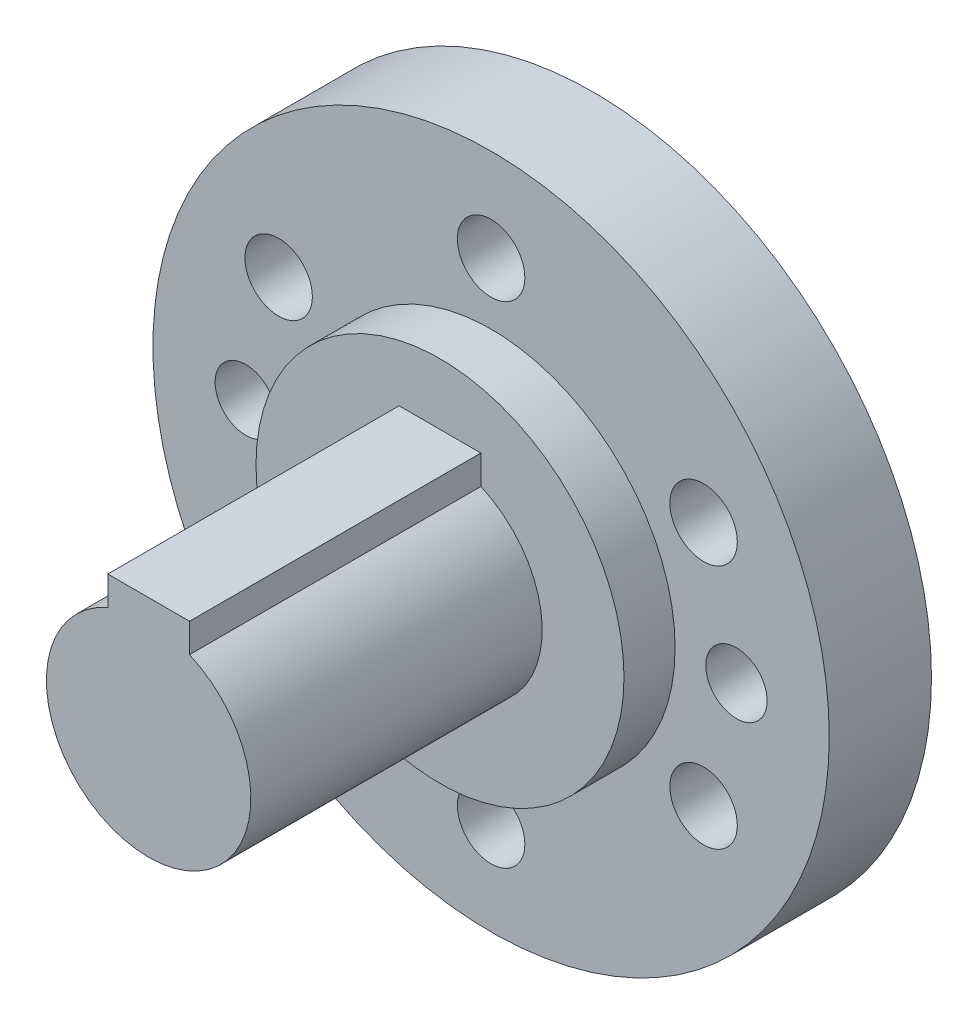
SolidWorks part; units mm, degrees
ref_plane "Front Plane" through (0, 0, 0) normal (0, 0, 1) x (1, 0, 0)
ref_plane "Top Plane" through (0, 0, 0) normal (0, 1, 0) x (1, 0, 0)
ref_plane "Right Plane" through (0, 0, 0) normal (1, 0, 0) x (0, 0, -1)
sketch "Sketch1" plane through (0, 0, 0) normal (0, 0, 1) x (1, 0, 0)
  arc A0 (9, 0) -> (-9, 0) centre (0, 0) ccw
  arc A1 (-9, 0) -> (9, 0) centre (0, 0) ccw
  arc A2 (1.65, 12) -> (-1.65, 12) centre (0, 12) ccw
  arc A3 (-1.65, 12) -> (1.65, 12) centre (0, 12) ccw
  arc A4 (11.2173, 4.5711) -> (9.5673, 7.4289) centre (10.3923, 6) ccw
  arc A5 (9.5673, 7.4289) -> (11.2173, 4.5711) centre (10.3923, 6) ccw
  arc A6 (9.5673, -7.4289) -> (11.2173, -4.5711) centre (10.3923, -6) ccw
  arc A7 (11.2173, -4.5711) -> (9.5673, -7.4289) centre (10.3923, -6) ccw
  arc A8 (-1.65, -12) -> (1.65, -12) centre (0, -12) ccw
  arc A9 (1.65, -12) -> (-1.65, -12) centre (0, -12) ccw
  arc A10 (-11.2173, -4.5711) -> (-9.5673, -7.4289) centre (-10.3923, -6) ccw
  arc A11 (-9.5673, -7.4289) -> (-11.2173, -4.5711) centre (-10.3923, -6) ccw
  arc A12 (-9.5673, 7.4289) -> (-11.2173, 4.5711) centre (-10.3923, 6) ccw
  arc A13 (-11.2173, 4.5711) -> (-9.5673, 7.4289) centre (-10.3923, 6) ccw
  arc A14 (13.5, 0) -> (10.5, 0) centre (12, 0) ccw
  arc A15 (10.5, 0) -> (13.5, 0) centre (12, 0) ccw
  arc A16 (-10.5, 0) -> (-13.5, 0) centre (-12, 0) ccw
  arc A17 (-13.5, 0) -> (-10.5, 0) centre (-12, 0) ccw
  circle A18 centre (0, 0) radius 16.5398
  dimension "D1" = 9
  dimension "D3" = 1.65
  dimension "D4" = 1.65
  dimension "D2" = 12
extrude "Boss-Extrude1" add sketch "Sketch1" along normal mid plane 5
sketch "Sketch3" plane through (0, 0, 2.5) normal (0, 0, 1) x (1, 0, 0)
  circle A1 centre (0, 0) radius 9
extrude "Boss-Extrude3" add sketch "Sketch3" along normal mid plane 5
sketch "Sketch4" plane through (0, 0, 5) normal (0, 0, 1) x (1, 0, 0)
  line L2 (-2, 4.5826) -> (-2, 6)
  line L3 (-2, 6) -> (2, 6)
  line L4 (2, 4.5826) -> (2, 6)
  arc A0 (-2, 4.5826) -> (2, 4.5826) centre (0, 0) ccw
  point P3 (0, 5)
  dimension "D1" = 10
  dimension "D2" = 2
  dimension "D3" = 4
  dimension "D4" = 6
extrude "Boss-Extrude5" add sketch "Sketch4" along normal blind 14.25
